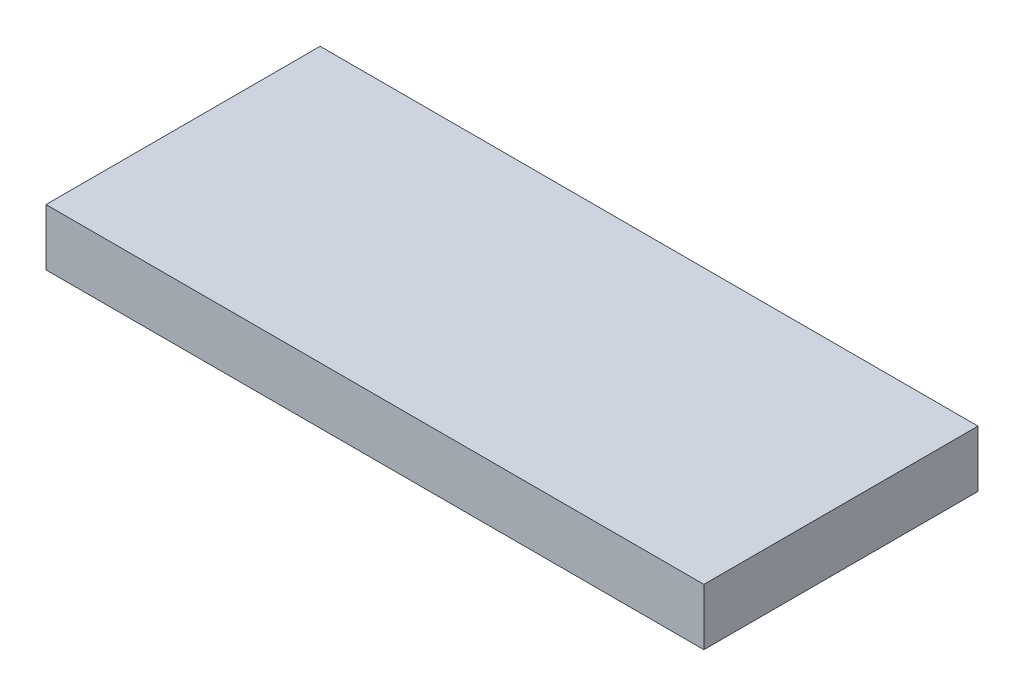
SolidWorks part; units mm, degrees
material "Boîtes en carton ondulé"
ref_plane "Plan de face" through (0, 0, 0) normal (0, 0, 1) x (1, 0, 0)
ref_plane "Plan de dessus" through (0, 0, 0) normal (0, 1, 0) x (1, 0, 0)
ref_plane "Plan de droite" through (0, 0, 0) normal (1, 0, 0) x (0, 0, -1)
sketch "Esquisse1" plane through (0, 0, 0) normal (0, 1, 0) x (1, 0, 0)
  line L1 (-186, -77.5) -> (186, -77.5)
  line L2 (-186, -77.5) -> (-186, 77.5)
  line L3 (-186, 77.5) -> (186, 77.5)
  line L4 (186, -77.5) -> (186, 77.5)
  line L5 (-186, -77.5) -> (186, 77.5) construction
  line L6 (-186, 77.5) -> (186, -77.5) construction
  point P0 (0, 0)
  dimension "D1" = 155
  dimension "D2" = 372
extrude "Boss.-Extru.1" add sketch "Esquisse1" along normal blind 32
